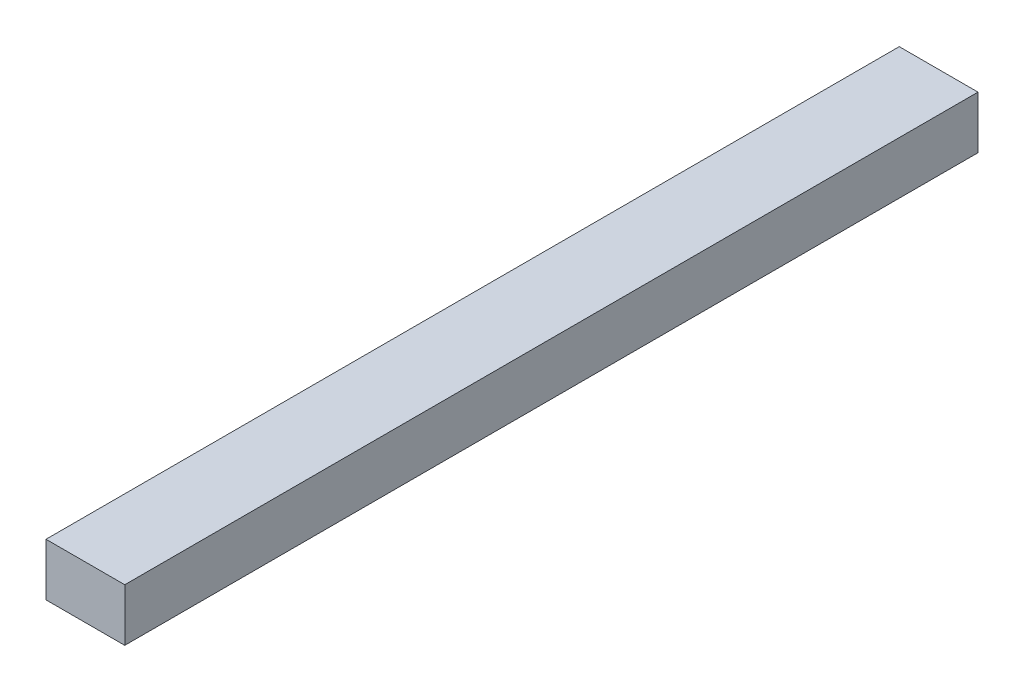
SolidWorks part; units mm, degrees
ref_plane "Front Plane" through (0, 0, 0) normal (0, 0, 1) x (1, 0, 0)
ref_plane "Top Plane" through (0, 0, 0) normal (0, 1, 0) x (1, 0, 0)
ref_plane "Right Plane" through (0, 0, 0) normal (1, 0, 0) x (0, 0, -1)
sketch "Sketch1" plane through (0, 0, 0) normal (0, 0, 1) x (1, 0, 0)
  line L1 (-22.8802, 33.4498) -> (97.1198, 33.4498)
  line L2 (-22.8802, 33.4498) -> (-22.8802, -46.5502)
  line L3 (-22.8802, -46.5502) -> (97.1198, -46.5502)
  line L4 (97.1198, 33.4498) -> (97.1198, -46.5502)
extrude "Boss-Extrude1" add sketch "Sketch1" along normal blind 1300
